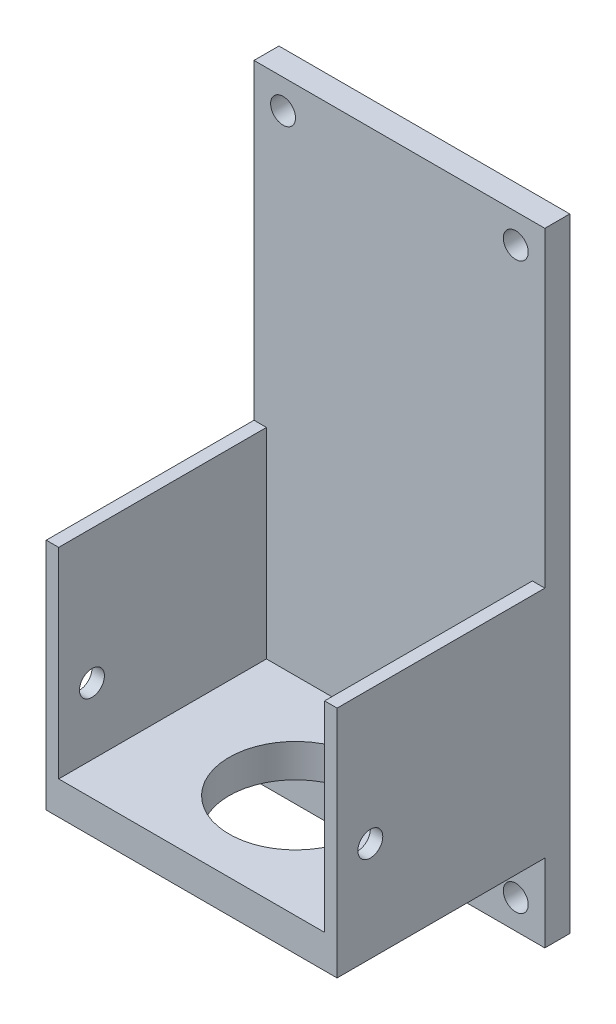
SolidWorks part; units mm, degrees
ref_plane "Front Plane" through (0, 0, 0) normal (0, 0, 1) x (1, 0, 0)
ref_plane "Top Plane" through (0, 0, 0) normal (0, 1, 0) x (1, 0, 0)
ref_plane "Right Plane" through (0, 0, 0) normal (1, 0, 0) x (0, 0, -1)
sketch "Sketch1" plane through (0, 0, 0) normal (0, 0, 1) x (1, 0, 0)
  line L1 (-17.5, -37.5) -> (17.5, -37.5)
  line L2 (-17.5, -37.5) -> (-17.5, 37.5)
  line L3 (-17.5, 37.5) -> (17.5, 37.5)
  line L4 (17.5, -37.5) -> (17.5, 37.5)
  line L5 (-17.5, -37.5) -> (17.5, 37.5) construction
  line L6 (-17.5, 37.5) -> (17.5, -37.5) construction
  point P0 (0, 0)
  dimension "D1" = 75
  dimension "D2" = 35
extrude "Boss-Extrude1" add sketch "Sketch1" along normal blind 3
sketch "Sketch2" plane through (0, 0, 3) normal (0, 0, 1) x (1, 0, 0)
  line L1 (-14, -34) -> (14, -34) construction
  line L2 (-14, -34) -> (-14, 34) construction
  line L3 (-14, 34) -> (14, 34) construction
  line L4 (14, -34) -> (14, 34) construction
  line L5 (-14, -34) -> (14, 34) construction
  line L6 (-14, 34) -> (14, -34) construction
  circle A0 centre (14, 34) radius 1.5
  circle A1 centre (-14, 34) radius 1.5
  circle A2 centre (14, -34) radius 1.5
  circle A3 centre (-14, -34) radius 1.5
  point P0 (0, 0)
  dimension "D1" = 3
  dimension "D2" = 68
  dimension "D3" = 28
extrude "side holes" cut sketch "Sketch2" against normal blind 13
sketch "Sketch3" plane through (0, 0, 3) normal (0, 0, 1) x (1, 0, 0)
  line L1 (-16, -28.1303) -> (16, -28.1303)
  line L2 (-16, -28.1303) -> (-16, -24.1303)
  line L3 (-16, -24.1303) -> (16, -24.1303)
  line L4 (16, -28.1303) -> (16, -24.1303)
  line L5 (-16, -28.1303) -> (16, -24.1303) construction
  line L6 (-16, -24.1303) -> (16, -28.1303) construction
  point P0 (0, -26.1303)
  dimension "D1" = 32
  dimension "D2" = 4
extrude "Boss-Extrude2" add sketch "Sketch3" along normal blind 25
sketch "Sketch4" plane through (0, -28.1303, 0) normal (0, -1, 0) x (1, 0, 0)
  line L0 (-16, 28) -> (16, 3) construction
  line L1 (-16, 3) -> (16, 3) construction
  circle A0 centre (0, 15.5) radius 8
  point P7 (0, 15.5)
  dimension "D1" = 16
extrude "Cut-Extrude2" cut sketch "Sketch4" against normal blind 5
sketch "Sketch5" plane through (-16, 0, 0) normal (-1, 0, 0) x (0, 0, 1)
  line L0 (28, -24.1303) -> (28, -28.1303) construction
  line L1 (3, -28.1303) -> (28, -28.1303)
  line L2 (3, -28.1303) -> (3, 0)
  line L3 (3, 0) -> (28, 0)
  line L4 (28, -28.1303) -> (28, 0)
extrude "Boss-Extrude3" add sketch "Sketch5" along normal up to surface (1.5 mm away) up to face at (-17.5, 0, 1.5)
sketch "Sketch6" plane through (16, 0, 0) normal (1, 0, 0) x (0, 0, -1)
  line L0 (-28, 0) -> (-3, 0) construction
  line L1 (-3, -28.1303) -> (-28, -28.1303)
  line L2 (-3, -28.1303) -> (-3, 0)
  line L3 (-3, 0) -> (-28, 0)
  line L4 (-28, -28.1303) -> (-28, 0)
  line L5 (-28, -28.1303) -> (-28, -24.1303) construction
extrude "Boss-Extrude4" add sketch "Sketch6" along normal up to surface (1.5 mm away) up to face at (17.5, 0, 1.5)
sketch "Sketch7" plane through (17.5, 0, 0) normal (1, 0, 0) x (0, 0, -1)
  line L0 (-3, -28.1303) -> (-28, -28.1303) construction
  line L1 (-28, -28.1303) -> (-28, 0) construction
  circle A0 centre (-24, -16.1303) radius 1.5
  point P2 (-24.4358, -15.4373)
  dimension "D1" = 3
  dimension "D2" = 12
  dimension "D3" = 4
extrude "Cut-Extrude3" cut sketch "Sketch7" against normal through all
